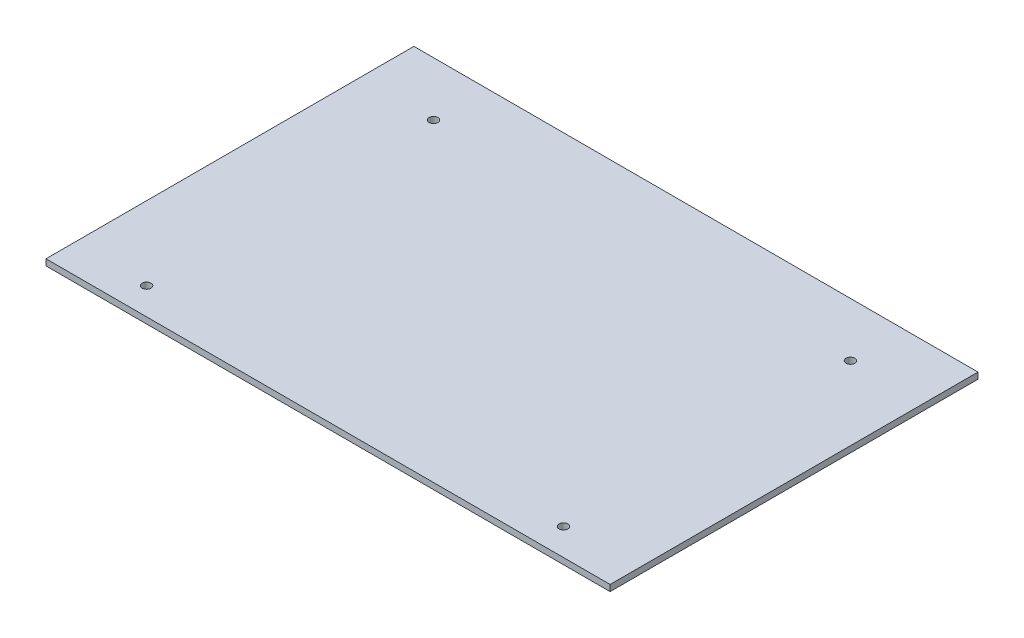
SolidWorks part; units mm, degrees
ref_plane "Alzado" through (0, 0, 0) normal (0, 0, 1) x (1, 0, 0)
ref_plane "Planta" through (0, 0, 0) normal (0, 1, 0) x (1, 0, 0)
ref_plane "Vista lateral" through (0, 0, 0) normal (1, 0, 0) x (0, 0, -1)
sketch "Croquis2" plane through (0, 0, 0) normal (0, 1, 0) x (1, 0, 0)
  line L1 (0, 0) -> (1150, 0)
  line L2 (0, 0) -> (0, -750)
  line L3 (0, -750) -> (1150, -750)
  line L4 (1150, 0) -> (1150, -750)
  dimension "D1" = 1150
  dimension "D2" = 750
extrude "Saliente-Extruir1" add sketch "Croquis2" along normal blind 12.7
sketch "Croquis7" plane through (0, 12.7, 0) normal (0, 1, 0) x (1, 0, 0)
  line L0 (575, -750) -> (575, 0) construction
  line L1 (0, -750) -> (1150, -750) construction
  line L2 (1150, 0) -> (0, 0) construction
  line L3 (1150, -375) -> (0, -375) construction
  line L4 (1150, -750) -> (1150, 0) construction
  line L5 (0, 0) -> (0, -750) construction
  circle A0 centre (1000, -110) radius 9
  circle A1 centre (150, -110) radius 9
  circle A2 centre (1000, -695) radius 9
  circle A3 centre (150, -695) radius 9
  dimension "D1" = 18
  dimension "D2" = 18
  dimension "D7" = 18
  dimension "D8" = 18
  dimension "D9" = 425
  dimension "D10" = 320
  dimension "D12" = 320
  dimension "D3" = 425
  dimension "D4" = 265
  dimension "D5" = 425
  dimension "D6" = 265
  dimension "D11" = 425
extrude "Cortar-Extruir1" cut sketch "Croquis7" against normal blind 120
